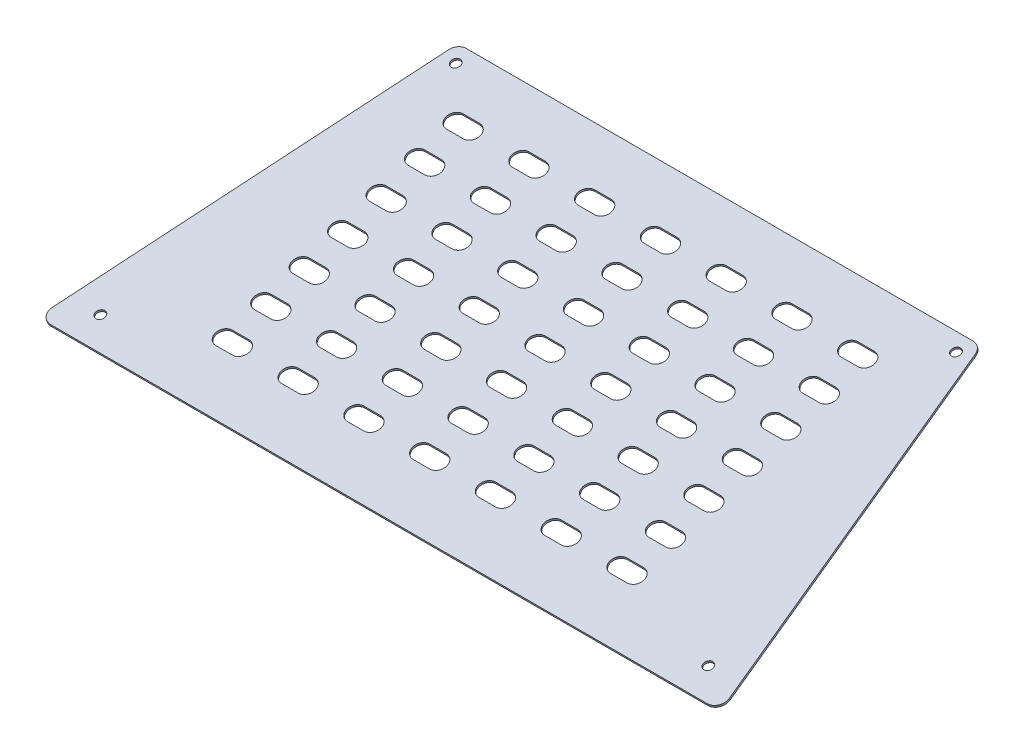
SolidWorks part; units mm, degrees
material "6061 Alloy"
ref_plane "Front Plane" through (0, 0, 0) normal (0, 0, 1) x (1, 0, 0)
ref_plane "Top Plane" through (0, 0, 0) normal (0, 1, 0) x (1, 0, 0)
ref_plane "Right Plane" through (0, 0, 0) normal (1, 0, 0) x (0, 0, -1)
ref_plane "Plane1" through (0, 394.1737, 122.8593) normal (0, 0.9547, 0.2976) x (1, 0, 0)
sketch "Sketch2" plane through (0, 394.1737, 122.8593) normal (0, 0.9547, 0.2976) x (1, 0, 0)
  line L0 (-128.1784, 873.4157) -> (-164.6929, 709.7817)
  line L1 (-159.813, 703.6928) -> (159.813, 703.6928)
  line L2 (164.6929, 709.7817) -> (128.1784, 873.4157)
  line L3 (123.2984, 877.3267) -> (-123.2984, 877.3267)
  line L4 (-180, 691.6928) -> (-135.0058, 893.3267) construction
  line L5 (180, 691.6928) -> (135.0058, 893.3267) construction
  line L6 (-135.0058, 893.3267) -> (135.0058, 893.3267) construction
  line L7 (-185, 691.6928) -> (185, 691.6928) construction
  circle A0 centre (-121.6955, 870.3267) radius 2.25 construction
  circle A1 centre (-121.6955, 870.3267) radius 2.25
  circle A2 centre (121.6955, 870.3267) radius 2.25 construction
  circle A3 centre (121.6955, 870.3267) radius 2.25
  circle A4 centre (147.891, 716.6928) radius 2.25 construction
  circle A5 centre (147.891, 716.6928) radius 2.25
  circle A6 centre (-147.891, 716.6928) radius 2.25 construction
  circle A7 centre (-147.891, 716.6928) radius 2.25
  arc A8 (159.813, 703.6928) -> (164.6929, 709.7817) centre (159.813, 708.6928) ccw
  arc A9 (128.1784, 873.4157) -> (123.2984, 877.3267) centre (123.2984, 872.3267) ccw
  arc A10 (-128.1784, 873.4157) -> (-123.2984, 877.3267) centre (-123.2984, 872.3267) cw
  arc A11 (-164.6929, 709.7817) -> (-159.813, 703.6928) centre (-159.813, 708.6928) ccw
  dimension "D5" = 5
  dimension "D1" = 12
  dimension "D2" = 16
  dimension "D3" = 11
  dimension "D4" = 11
extrude "Boss-Extrude1" add sketch "Sketch2" along normal blind 1 from surface at 1
sketch "Sketch3" plane through (0, 396.0831, 123.4545) normal (0, 0.9547, 0.2976) x (1, 0, 0)
  line L0 (-103.1885, 854.7267) -> (-95.1885, 854.7267)
  line L1 (-103.1885, 846.3267) -> (-95.1885, 846.3267)
  line L2 (123.2984, 877.3267) -> (-123.2984, 877.3267) construction
  line L3 (-128.1784, 873.4157) -> (-164.6929, 709.7817) construction
  line L4 (-71.1885, 854.7267) -> (-63.1885, 854.7267)
  line L5 (-71.1885, 846.3267) -> (-63.1885, 846.3267)
  line L6 (-39.1885, 854.7267) -> (-31.1885, 854.7267)
  line L7 (-39.1885, 846.3267) -> (-31.1885, 846.3267)
  line L8 (-7.1885, 854.7267) -> (0.8115, 854.7267)
  line L9 (-7.1885, 846.3267) -> (0.8115, 846.3267)
  line L10 (24.8115, 854.7267) -> (32.8115, 854.7267)
  line L11 (24.8115, 846.3267) -> (32.8115, 846.3267)
  line L12 (56.8115, 854.7267) -> (64.8115, 854.7267)
  line L13 (56.8115, 846.3267) -> (64.8115, 846.3267)
  line L14 (88.8115, 854.7267) -> (96.8115, 854.7267)
  line L15 (88.8115, 846.3267) -> (96.8115, 846.3267)
  line L16 (-71.1885, 835.1267) -> (-63.1885, 835.1267)
  line L17 (-71.1885, 826.7267) -> (-63.1885, 826.7267)
  line L18 (-39.1885, 835.1267) -> (-31.1885, 835.1267)
  line L19 (-39.1885, 826.7267) -> (-31.1885, 826.7267)
  line L20 (-7.1885, 835.1267) -> (0.8115, 835.1267)
  line L21 (-7.1885, 826.7267) -> (0.8115, 826.7267)
  line L22 (24.8115, 835.1267) -> (32.8115, 835.1267)
  line L23 (24.8115, 826.7267) -> (32.8115, 826.7267)
  line L24 (56.8115, 835.1267) -> (64.8115, 835.1267)
  line L25 (56.8115, 826.7267) -> (64.8115, 826.7267)
  line L26 (88.8115, 835.1267) -> (96.8115, 835.1267)
  line L27 (88.8115, 826.7267) -> (96.8115, 826.7267)
  line L28 (-71.1885, 815.5267) -> (-63.1885, 815.5267)
  line L29 (-71.1885, 807.1267) -> (-63.1885, 807.1267)
  line L30 (-39.1885, 815.5267) -> (-31.1885, 815.5267)
  line L31 (-39.1885, 807.1267) -> (-31.1885, 807.1267)
  line L32 (-7.1885, 815.5267) -> (0.8115, 815.5267)
  line L33 (-7.1885, 807.1267) -> (0.8115, 807.1267)
  line L34 (24.8115, 815.5267) -> (32.8115, 815.5267)
  line L35 (24.8115, 807.1267) -> (32.8115, 807.1267)
  line L36 (56.8115, 815.5267) -> (64.8115, 815.5267)
  line L37 (56.8115, 807.1267) -> (64.8115, 807.1267)
  line L38 (88.8115, 815.5267) -> (96.8115, 815.5267)
  line L39 (88.8115, 807.1267) -> (96.8115, 807.1267)
  line L40 (-71.1885, 795.9267) -> (-63.1885, 795.9267)
  line L41 (-71.1885, 787.5267) -> (-63.1885, 787.5267)
  line L42 (-39.1885, 795.9267) -> (-31.1885, 795.9267)
  line L43 (-39.1885, 787.5267) -> (-31.1885, 787.5267)
  line L44 (-7.1885, 795.9267) -> (0.8115, 795.9267)
  line L45 (-7.1885, 787.5267) -> (0.8115, 787.5267)
  line L46 (24.8115, 795.9267) -> (32.8115, 795.9267)
  line L47 (24.8115, 787.5267) -> (32.8115, 787.5267)
  line L48 (56.8115, 795.9267) -> (64.8115, 795.9267)
  line L49 (56.8115, 787.5267) -> (64.8115, 787.5267)
  line L50 (88.8115, 795.9267) -> (96.8115, 795.9267)
  line L51 (88.8115, 787.5267) -> (96.8115, 787.5267)
  line L52 (-71.1885, 776.3267) -> (-63.1885, 776.3267)
  line L53 (-71.1885, 767.9267) -> (-63.1885, 767.9267)
  line L54 (-39.1885, 776.3267) -> (-31.1885, 776.3267)
  line L55 (-39.1885, 767.9267) -> (-31.1885, 767.9267)
  line L56 (-7.1885, 776.3267) -> (0.8115, 776.3267)
  line L57 (-7.1885, 767.9267) -> (0.8115, 767.9267)
  line L58 (24.8115, 776.3267) -> (32.8115, 776.3267)
  line L59 (24.8115, 767.9267) -> (32.8115, 767.9267)
  line L60 (56.8115, 776.3267) -> (64.8115, 776.3267)
  line L61 (56.8115, 767.9267) -> (64.8115, 767.9267)
  line L62 (88.8115, 776.3267) -> (96.8115, 776.3267)
  line L63 (88.8115, 767.9267) -> (96.8115, 767.9267)
  line L64 (-71.1885, 756.7267) -> (-63.1885, 756.7267)
  line L65 (-71.1885, 748.3267) -> (-63.1885, 748.3267)
  line L66 (-39.1885, 756.7267) -> (-31.1885, 756.7267)
  line L67 (-39.1885, 748.3267) -> (-31.1885, 748.3267)
  line L68 (-7.1885, 756.7267) -> (0.8115, 756.7267)
  line L69 (-7.1885, 748.3267) -> (0.8115, 748.3267)
  line L70 (24.8115, 756.7267) -> (32.8115, 756.7267)
  line L71 (24.8115, 748.3267) -> (32.8115, 748.3267)
  line L72 (56.8115, 756.7267) -> (64.8115, 756.7267)
  line L73 (56.8115, 748.3267) -> (64.8115, 748.3267)
  line L74 (88.8115, 756.7267) -> (96.8115, 756.7267)
  line L75 (88.8115, 748.3267) -> (96.8115, 748.3267)
  line L76 (-71.1885, 737.1267) -> (-63.1885, 737.1267)
  line L77 (-71.1885, 728.7267) -> (-63.1885, 728.7267)
  line L78 (-39.1885, 737.1267) -> (-31.1885, 737.1267)
  line L79 (-39.1885, 728.7267) -> (-31.1885, 728.7267)
  line L80 (-7.1885, 737.1267) -> (0.8115, 737.1267)
  line L81 (-7.1885, 728.7267) -> (0.8115, 728.7267)
  line L82 (24.8115, 737.1267) -> (32.8115, 737.1267)
  line L83 (24.8115, 728.7267) -> (32.8115, 728.7267)
  line L84 (56.8115, 737.1267) -> (64.8115, 737.1267)
  line L85 (56.8115, 728.7267) -> (64.8115, 728.7267)
  line L86 (88.8115, 737.1267) -> (96.8115, 737.1267)
  line L87 (88.8115, 728.7267) -> (96.8115, 728.7267)
  line L88 (-103.1885, 835.1267) -> (-95.1885, 835.1267)
  line L89 (-103.1885, 826.7267) -> (-95.1885, 826.7267)
  line L90 (-103.1885, 815.5267) -> (-95.1885, 815.5267)
  line L91 (-103.1885, 807.1267) -> (-95.1885, 807.1267)
  line L92 (-103.1885, 795.9267) -> (-95.1885, 795.9267)
  line L93 (-103.1885, 787.5267) -> (-95.1885, 787.5267)
  line L94 (-103.1885, 776.3267) -> (-95.1885, 776.3267)
  line L95 (-103.1885, 767.9267) -> (-95.1885, 767.9267)
  line L96 (-103.1885, 756.7267) -> (-95.1885, 756.7267)
  line L97 (-103.1885, 748.3267) -> (-95.1885, 748.3267)
  line L98 (-103.1885, 737.1267) -> (-95.1885, 737.1267)
  line L99 (-103.1885, 728.7267) -> (-95.1885, 728.7267)
  arc A0 (-95.1885, 846.3267) -> (-95.1885, 854.7267) centre (-95.1885, 850.5267) ccw
  arc A1 (-103.1885, 854.7267) -> (-103.1885, 846.3267) centre (-103.1885, 850.5267) ccw
  arc A2 (-63.1885, 846.3267) -> (-63.1885, 854.7267) centre (-63.1885, 850.5267) ccw
  arc A3 (-71.1885, 854.7267) -> (-71.1885, 846.3267) centre (-71.1885, 850.5267) ccw
  arc A4 (-31.1885, 846.3267) -> (-31.1885, 854.7267) centre (-31.1885, 850.5267) ccw
  arc A5 (-39.1885, 854.7267) -> (-39.1885, 846.3267) centre (-39.1885, 850.5267) ccw
  arc A6 (0.8115, 846.3267) -> (0.8115, 854.7267) centre (0.8115, 850.5267) ccw
  arc A7 (-7.1885, 854.7267) -> (-7.1885, 846.3267) centre (-7.1885, 850.5267) ccw
  arc A8 (32.8115, 846.3267) -> (32.8115, 854.7267) centre (32.8115, 850.5267) ccw
  arc A9 (24.8115, 854.7267) -> (24.8115, 846.3267) centre (24.8115, 850.5267) ccw
  arc A10 (64.8115, 846.3267) -> (64.8115, 854.7267) centre (64.8115, 850.5267) ccw
  arc A11 (56.8115, 854.7267) -> (56.8115, 846.3267) centre (56.8115, 850.5267) ccw
  arc A12 (96.8115, 846.3267) -> (96.8115, 854.7267) centre (96.8115, 850.5267) ccw
  arc A13 (88.8115, 854.7267) -> (88.8115, 846.3267) centre (88.8115, 850.5267) ccw
  arc A14 (-63.1885, 826.7267) -> (-63.1885, 835.1267) centre (-63.1885, 830.9267) ccw
  arc A15 (-71.1885, 835.1267) -> (-71.1885, 826.7267) centre (-71.1885, 830.9267) ccw
  arc A16 (-31.1885, 826.7267) -> (-31.1885, 835.1267) centre (-31.1885, 830.9267) ccw
  arc A17 (-39.1885, 835.1267) -> (-39.1885, 826.7267) centre (-39.1885, 830.9267) ccw
  arc A18 (0.8115, 826.7267) -> (0.8115, 835.1267) centre (0.8115, 830.9267) ccw
  arc A19 (-7.1885, 835.1267) -> (-7.1885, 826.7267) centre (-7.1885, 830.9267) ccw
  arc A20 (32.8115, 826.7267) -> (32.8115, 835.1267) centre (32.8115, 830.9267) ccw
  arc A21 (24.8115, 835.1267) -> (24.8115, 826.7267) centre (24.8115, 830.9267) ccw
  arc A22 (64.8115, 826.7267) -> (64.8115, 835.1267) centre (64.8115, 830.9267) ccw
  arc A23 (56.8115, 835.1267) -> (56.8115, 826.7267) centre (56.8115, 830.9267) ccw
  arc A24 (96.8115, 826.7267) -> (96.8115, 835.1267) centre (96.8115, 830.9267) ccw
  arc A25 (88.8115, 835.1267) -> (88.8115, 826.7267) centre (88.8115, 830.9267) ccw
  arc A26 (-63.1885, 807.1267) -> (-63.1885, 815.5267) centre (-63.1885, 811.3267) ccw
  arc A27 (-71.1885, 815.5267) -> (-71.1885, 807.1267) centre (-71.1885, 811.3267) ccw
  arc A28 (-31.1885, 807.1267) -> (-31.1885, 815.5267) centre (-31.1885, 811.3267) ccw
  arc A29 (-39.1885, 815.5267) -> (-39.1885, 807.1267) centre (-39.1885, 811.3267) ccw
  arc A30 (0.8115, 807.1267) -> (0.8115, 815.5267) centre (0.8115, 811.3267) ccw
  arc A31 (-7.1885, 815.5267) -> (-7.1885, 807.1267) centre (-7.1885, 811.3267) ccw
  arc A32 (32.8115, 807.1267) -> (32.8115, 815.5267) centre (32.8115, 811.3267) ccw
  arc A33 (24.8115, 815.5267) -> (24.8115, 807.1267) centre (24.8115, 811.3267) ccw
  arc A34 (64.8115, 807.1267) -> (64.8115, 815.5267) centre (64.8115, 811.3267) ccw
  arc A35 (56.8115, 815.5267) -> (56.8115, 807.1267) centre (56.8115, 811.3267) ccw
  arc A36 (96.8115, 807.1267) -> (96.8115, 815.5267) centre (96.8115, 811.3267) ccw
  arc A37 (88.8115, 815.5267) -> (88.8115, 807.1267) centre (88.8115, 811.3267) ccw
  arc A38 (-63.1885, 787.5267) -> (-63.1885, 795.9267) centre (-63.1885, 791.7267) ccw
  arc A39 (-71.1885, 795.9267) -> (-71.1885, 787.5267) centre (-71.1885, 791.7267) ccw
  arc A40 (-31.1885, 787.5267) -> (-31.1885, 795.9267) centre (-31.1885, 791.7267) ccw
  arc A41 (-39.1885, 795.9267) -> (-39.1885, 787.5267) centre (-39.1885, 791.7267) ccw
  arc A42 (0.8115, 787.5267) -> (0.8115, 795.9267) centre (0.8115, 791.7267) ccw
  arc A43 (-7.1885, 795.9267) -> (-7.1885, 787.5267) centre (-7.1885, 791.7267) ccw
  arc A44 (32.8115, 787.5267) -> (32.8115, 795.9267) centre (32.8115, 791.7267) ccw
  arc A45 (24.8115, 795.9267) -> (24.8115, 787.5267) centre (24.8115, 791.7267) ccw
  arc A46 (64.8115, 787.5267) -> (64.8115, 795.9267) centre (64.8115, 791.7267) ccw
  arc A47 (56.8115, 795.9267) -> (56.8115, 787.5267) centre (56.8115, 791.7267) ccw
  arc A48 (96.8115, 787.5267) -> (96.8115, 795.9267) centre (96.8115, 791.7267) ccw
  arc A49 (88.8115, 795.9267) -> (88.8115, 787.5267) centre (88.8115, 791.7267) ccw
  arc A50 (-63.1885, 767.9267) -> (-63.1885, 776.3267) centre (-63.1885, 772.1267) ccw
  arc A51 (-71.1885, 776.3267) -> (-71.1885, 767.9267) centre (-71.1885, 772.1267) ccw
  arc A52 (-31.1885, 767.9267) -> (-31.1885, 776.3267) centre (-31.1885, 772.1267) ccw
  arc A53 (-39.1885, 776.3267) -> (-39.1885, 767.9267) centre (-39.1885, 772.1267) ccw
  arc A54 (0.8115, 767.9267) -> (0.8115, 776.3267) centre (0.8115, 772.1267) ccw
  arc A55 (-7.1885, 776.3267) -> (-7.1885, 767.9267) centre (-7.1885, 772.1267) ccw
  arc A56 (32.8115, 767.9267) -> (32.8115, 776.3267) centre (32.8115, 772.1267) ccw
  arc A57 (24.8115, 776.3267) -> (24.8115, 767.9267) centre (24.8115, 772.1267) ccw
  arc A58 (64.8115, 767.9267) -> (64.8115, 776.3267) centre (64.8115, 772.1267) ccw
  arc A59 (56.8115, 776.3267) -> (56.8115, 767.9267) centre (56.8115, 772.1267) ccw
  arc A60 (96.8115, 767.9267) -> (96.8115, 776.3267) centre (96.8115, 772.1267) ccw
  arc A61 (88.8115, 776.3267) -> (88.8115, 767.9267) centre (88.8115, 772.1267) ccw
  arc A62 (-63.1885, 748.3267) -> (-63.1885, 756.7267) centre (-63.1885, 752.5267) ccw
  arc A63 (-71.1885, 756.7267) -> (-71.1885, 748.3267) centre (-71.1885, 752.5267) ccw
  arc A64 (-31.1885, 748.3267) -> (-31.1885, 756.7267) centre (-31.1885, 752.5267) ccw
  arc A65 (-39.1885, 756.7267) -> (-39.1885, 748.3267) centre (-39.1885, 752.5267) ccw
  arc A66 (0.8115, 748.3267) -> (0.8115, 756.7267) centre (0.8115, 752.5267) ccw
  arc A67 (-7.1885, 756.7267) -> (-7.1885, 748.3267) centre (-7.1885, 752.5267) ccw
  arc A68 (32.8115, 748.3267) -> (32.8115, 756.7267) centre (32.8115, 752.5267) ccw
  arc A69 (24.8115, 756.7267) -> (24.8115, 748.3267) centre (24.8115, 752.5267) ccw
  arc A70 (64.8115, 748.3267) -> (64.8115, 756.7267) centre (64.8115, 752.5267) ccw
  arc A71 (56.8115, 756.7267) -> (56.8115, 748.3267) centre (56.8115, 752.5267) ccw
  arc A72 (96.8115, 748.3267) -> (96.8115, 756.7267) centre (96.8115, 752.5267) ccw
  arc A73 (88.8115, 756.7267) -> (88.8115, 748.3267) centre (88.8115, 752.5267) ccw
  arc A74 (-63.1885, 728.7267) -> (-63.1885, 737.1267) centre (-63.1885, 732.9267) ccw
  arc A75 (-71.1885, 737.1267) -> (-71.1885, 728.7267) centre (-71.1885, 732.9267) ccw
  arc A76 (-31.1885, 728.7267) -> (-31.1885, 737.1267) centre (-31.1885, 732.9267) ccw
  arc A77 (-39.1885, 737.1267) -> (-39.1885, 728.7267) centre (-39.1885, 732.9267) ccw
  arc A78 (0.8115, 728.7267) -> (0.8115, 737.1267) centre (0.8115, 732.9267) ccw
  arc A79 (-7.1885, 737.1267) -> (-7.1885, 728.7267) centre (-7.1885, 732.9267) ccw
  arc A80 (32.8115, 728.7267) -> (32.8115, 737.1267) centre (32.8115, 732.9267) ccw
  arc A81 (24.8115, 737.1267) -> (24.8115, 728.7267) centre (24.8115, 732.9267) ccw
  arc A82 (64.8115, 728.7267) -> (64.8115, 737.1267) centre (64.8115, 732.9267) ccw
  arc A83 (56.8115, 737.1267) -> (56.8115, 728.7267) centre (56.8115, 732.9267) ccw
  arc A84 (96.8115, 728.7267) -> (96.8115, 737.1267) centre (96.8115, 732.9267) ccw
  arc A85 (88.8115, 737.1267) -> (88.8115, 728.7267) centre (88.8115, 732.9267) ccw
  arc A86 (-95.1885, 826.7267) -> (-95.1885, 835.1267) centre (-95.1885, 830.9267) ccw
  arc A87 (-103.1885, 835.1267) -> (-103.1885, 826.7267) centre (-103.1885, 830.9267) ccw
  arc A88 (-95.1885, 807.1267) -> (-95.1885, 815.5267) centre (-95.1885, 811.3267) ccw
  arc A89 (-103.1885, 815.5267) -> (-103.1885, 807.1267) centre (-103.1885, 811.3267) ccw
  arc A90 (-95.1885, 787.5267) -> (-95.1885, 795.9267) centre (-95.1885, 791.7267) ccw
  arc A91 (-103.1885, 795.9267) -> (-103.1885, 787.5267) centre (-103.1885, 791.7267) ccw
  arc A92 (-95.1885, 767.9267) -> (-95.1885, 776.3267) centre (-95.1885, 772.1267) ccw
  arc A93 (-103.1885, 776.3267) -> (-103.1885, 767.9267) centre (-103.1885, 772.1267) ccw
  arc A94 (-95.1885, 748.3267) -> (-95.1885, 756.7267) centre (-95.1885, 752.5267) ccw
  arc A95 (-103.1885, 756.7267) -> (-103.1885, 748.3267) centre (-103.1885, 752.5267) ccw
  arc A96 (-95.1885, 728.7267) -> (-95.1885, 737.1267) centre (-95.1885, 732.9267) ccw
  arc A97 (-103.1885, 737.1267) -> (-103.1885, 728.7267) centre (-103.1885, 732.9267) ccw
  dimension "D1" = 8.4
  dimension "D2" = 8.4
  dimension "D5" = 29.375
  dimension "D3" = 8
  dimension "D4" = 22.6
  dimension "D6" = 7
  dimension "D7" = 7
extrude "Cut-Extrude1" cut sketch "Sketch3" against normal blind 1
